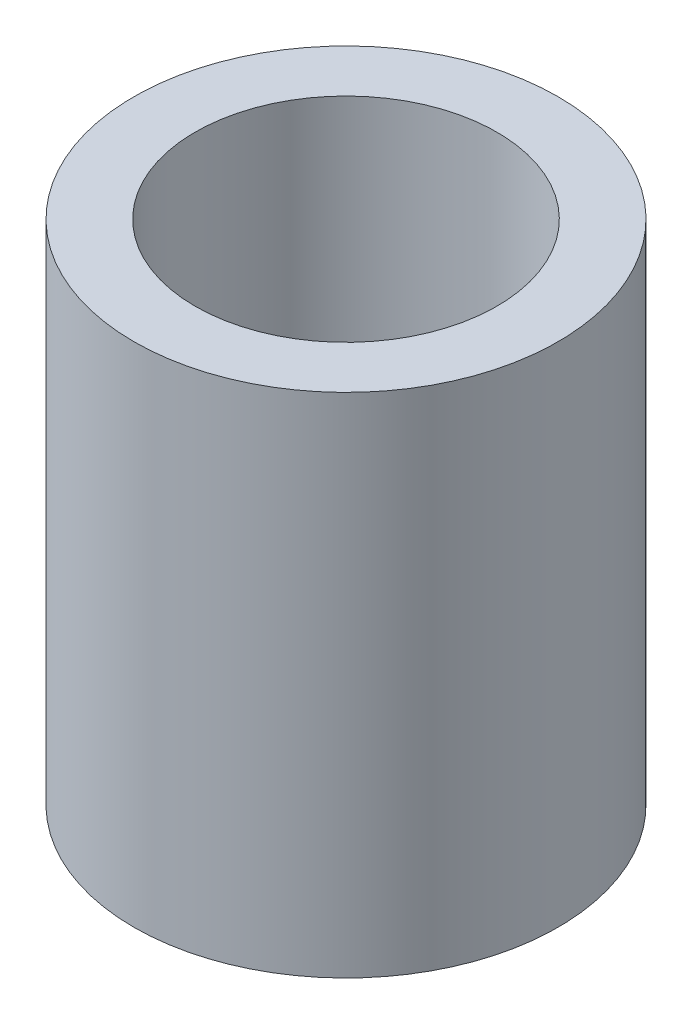
SolidWorks part; units mm, degrees
material "1060 Alloy"
ref_plane "Front Plane" through (0, 0, 0) normal (0, 0, 1) x (1, 0, 0)
ref_plane "Top Plane" through (0, 0, 0) normal (0, 1, 0) x (1, 0, 0)
ref_plane "Right Plane" through (0, 0, 0) normal (1, 0, 0) x (0, 0, -1)
sketch "Sketch1" plane through (0, 0, 0) normal (0, 1, 0) x (1, 0, 0)
  circle A0 centre (0, 0) radius 2.25
  circle A1 centre (0, 0) radius 1.6
  dimension "D1" = 3.2
  dimension "D2" = 4.5
extrude "Boss-Extrude1" add sketch "Sketch1" along normal blind 5.379
equation "\"ID\"=0.003200"
equation "\"OD\"=0.004500"
equation "\"D1@Sketch1\"=\"ID\"*1000"
equation "\"D2@Sketch1\"=\"OD\"*1000"
equation "\"H\"=0.005379"
equation "\"D1@Boss-Extrude1\"=\"H\"*1000"
